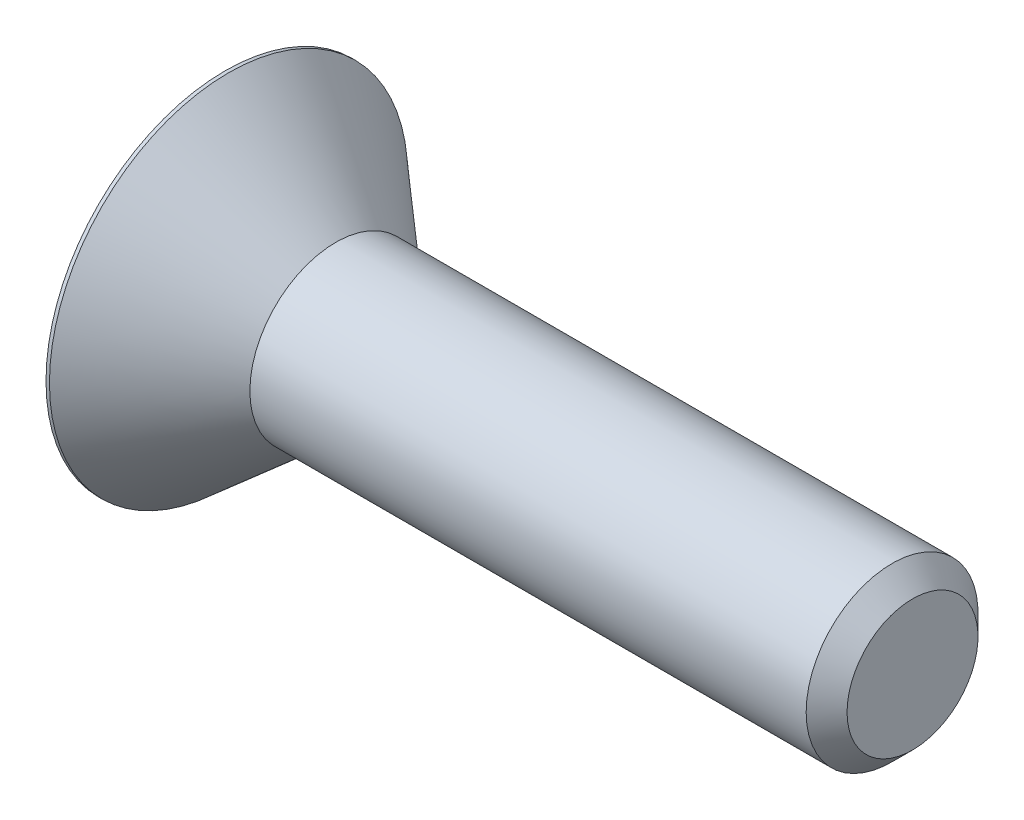
SolidWorks part; units mm, degrees
revolve "PreBroach" [suppressed] cut sketch "Sketch2"
sketch "Sketch2"
  line L0 (0, 1.9812) -> (2.8194, 1.9812)
  line L1 (2.8194, 1.9812) -> (3.9632, 0)
  line L2 (0, 0) -> (127, 0) construction
  line L3 (3.9632, 0) -> (0, 0)
  line L4 (0, 0) -> (0, 1.9812)
  line L5 (0, -1.9812) -> (2.8194, -1.9812) construction
  line L6 (0, 0) -> (47.625, 0) construction
  line L8 (0, 6.6192) -> (0, -6.6192) construction
  dimension "D2" = 60
revolve "BaseBody" add sketch "BodySke" angle 360 about L6
sketch "BodySke" plane through (0, 0, 0) normal (0, 0, 1) x (1, 0, 0)
  line L0 (0, 0) -> (0, 6.6192)
  line L1 (0.127, 6.6192) -> (4.0891, 3.175)
  line L2 (0, 6.6192) -> (0.127, 6.6192)
  line L3 (4.0891, 3.175) -> (24.6443, 3.175)
  line L4 (25.4, 2.4194) -> (25.4, 0)
  line L5 (25.4, 0) -> (0, 0)
  line L6 (0, 0) -> (127, 0) construction
  line L7 (0.127, -6.6192) -> (4.0891, -3.175) construction
  line L8 (25.4, 2.4194) -> (24.6443, 3.175)
  line L9 (0, -6.6192) -> (0.127, -6.6192) construction
  line L10 (25.4, -2.4194) -> (24.6443, -3.175) construction
  line L11 (5.3591, 9.525) -> (5.3591, -12.7) construction
  line L12 (0, 19.05) -> (0, -3.175) construction
  dimension "Body_ch_ang" = 45
  dimension "Diameter" = 6.35
  dimension "Minor_dia" = 4.8387
  dimension "Head_dia" = 13.2385
  dimension "Head_ang" = 82
  dimension "Length" = 25.4
  dimension "D1" = 0.127
  dimension "Advance" = 1.27
  dimension "Thread_nom" = 25.4
cosmetic thread "ThreadCosmetic"
ref_plane "Plane1" through (0, 0, 0) normal (0, 0, 1) x (1, 0, 0)
ref_plane "Plane2" through (0, 0, 0) normal (0, 1, 0) x (1, 0, 0)
ref_plane "Plane3" through (0, 0, 0) normal (1, 0, 0) x (0, 0, -1)
sketch "Sketch3" [suppressed] plane through (0, 0, 0) normal (-1, 0, 0) x (0, 0, 1)
  line L0 (-1.9812, -1.1438) -> (-1.9812, 1.1438)
  line L1 (-1.9812, 1.1438) -> (0, 2.2877)
  line L2 (0, 2.2877) -> (1.9812, 1.1438)
  line L3 (1.9812, 1.1438) -> (1.9812, -1.1438)
  line L4 (1.9812, -1.1438) -> (0, -2.2877)
  line L5 (0, -2.2877) -> (-1.9812, -1.1438)
  dimension "Hex_size" = 3.9624
  dimension "D1" = 1.9812
  dimension "D2" = 1.9812
  dimension "D3" = 3.9624
extrude "Hex" [suppressed] cut sketch "Sketch3" against normal blind 2.8194
sketch "Sketch4" plane through (0, 0, 0) normal (-1, 0, 0) x (0, 0, 1)
  line L0 (0, 0) -> (2.3876, 0)
  line L1 (0, 0) -> (6.1484, 3.5498) construction
  line L2 (0, 0) -> (1.1938, 2.0677)
  line L3 (1.9883, 0.576) -> (2.2704, 0.7389)
  line L4 (1.493, 1.4339) -> (1.7751, 1.5968)
  arc A0 (1.9883, 0.576) -> (1.493, 1.4339) centre (0, 0) ccw
  arc A1 (2.3876, 0) -> (2.2704, 0.7389) centre (0, 0) ccw
  arc A2 (1.1938, 2.0677) -> (1.7751, 1.5968) centre (0, 0) cw
  dimension "Spline_n_dim" = 4.1402
  dimension "Spline_m_dim" = 4.7752
  dimension "D1" = 30
  dimension "D2" = 60
  dimension "Spline_p_dim" = 0.9906
  dimension "D3" = 0.4953
extrude "Spline" [suppressed] cut sketch "Sketch4" against normal blind 2.8194
pattern_circular "CirPattern1" [suppressed] count 6 every 60 about axis through (0, 0, 0) along (1, 0, 0)
sketch "ThdSchSke" plane through (0, 0, 0) normal (0, 0, 1) x (1, 0, 0)
  line L0 (5.2322, -2.4194) -> (4.7031, -3.175)
  line L1 (5.2322, -2.4194) -> (5.7613, -3.175)
  line L2 (5.7613, -3.175) -> (5.7613, -3.9688)
  line L3 (-3.175, 0) -> (5.1513, 0) construction
  line L4 (0, 6.6192) -> (0, -6.6192) construction
  line L5 (5.7613, -3.9688) -> (4.7031, -3.9688)
  line L6 (4.7031, -3.9688) -> (4.7031, -3.175)
  dimension "Thread_minor" = 4.8387
  dimension "Diameter" = 6.35
  dimension "Start" = 5.2322
revolve "ThreadSchematic" [suppressed] cut sketch "ThdSchSke" angle 360 about L3
pattern_linear "ThdSchPat" [suppressed]
equation "\"D3@Sketch4\" = \"Spline_p_dim@Sketch4\" / 2"
equation "\"Thread_minor@ThreadCosmetic\"  =  \"Minor_dia@BodySke\""
equation "\"D2@CirPattern1\" = 360 / \"Num_teeth@CirPattern1\""
equation "\"D1@Sketch3\" = \"Hex_size@Sketch3\" / 2"
equation "\"D2@Sketch3\" = \"D1@Sketch3\""
equation "\"D3@Sketch3\" = \"Hex_size@Sketch3\""
equation "\"Thread_length@ThreadCosmetic\" = ((sgn( (\"Length@BodySke\" - \"Advance@BodySke\" - ( ( ( \"Head_dia@BodySke\" - \"Diameter@BodySke\" ) * 0.5 ) / tan( \"Head_ang@BodySke\" * 0.008726646 ) ) ) - \"Thread_nom@BodySke\" )-1)*( (\"Length@BodySke\" - \"Advance@BodySke\" - ( ( ( \"Head_dia@BodySke\" - \"Diameter@BodySke\" ) * 0.5 ) / tan( \"Head_ang@BodySke\" * 0.008726646 ) ) ) - \"Thread_nom@BodySke\" ))/-2+ \"Thread_nom@BodySke\""
equation "\"Thread_minor@ThdSchSke\" = \"Minor_dia@BodySke\""
equation "\"Diameter@ThdSchSke\" = \"Diameter@BodySke\""
equation "\"Overcut@ThdSchSke\" = \"Diameter@BodySke\" * 1.25"
equation "\"Start@ThdSchSke\" = 0.000001 + \"Length@BodySke\" - \"Thread_length@ThreadCosmetic\"  '---Countersunk---"
equation "\"Num_threads@ThdSchPat\" = int( \"Thread_length@ThreadCosmetic\" / \"Advance@BodySke\" + 0.999 )  + 1"
equation "\"Advance@ThdSchPat\" = \"Thread_length@ThreadCosmetic\" /  (\"Num_threads@ThdSchPat\" - 1) 'relax it"
equation "\"Num_threads@ThdSchPat\" = \"Num_threads@ThdSchPat\" - sgn( \"Num_threads@ThdSchPat\" - 1) '---chamfered tips only---"
